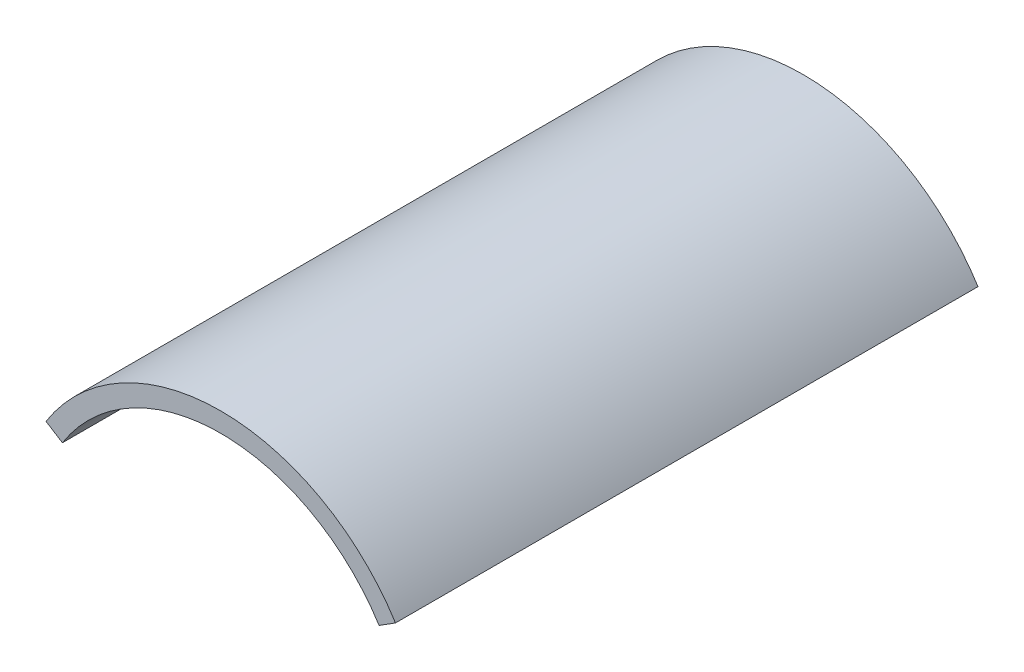
SolidWorks part; units mm, degrees
ref_plane "Front Plane" through (0, 0, 0) normal (0, 0, 1) x (1, 0, 0)
ref_plane "Top Plane" through (0, 0, 0) normal (0, 1, 0) x (1, 0, 0)
ref_plane "Right Plane" through (0, 0, 0) normal (1, 0, 0) x (0, 0, -1)
sketch "Sketch1" plane through (0, 0, 0) normal (0, 0, 1) x (1, 0, 0)
  arc A0 (-43.4062, -0.4329) -> (46.5938, -0.3935) centre (1.6062, -28.7994) cw
  point P4 (46.5938, -0.1968)
  point P5 (-59.8163, -0.4132)
  dimension "D1" = 90
extrude "Extrude-Thin1" add sketch "Sketch1" along normal blind 150 thin
